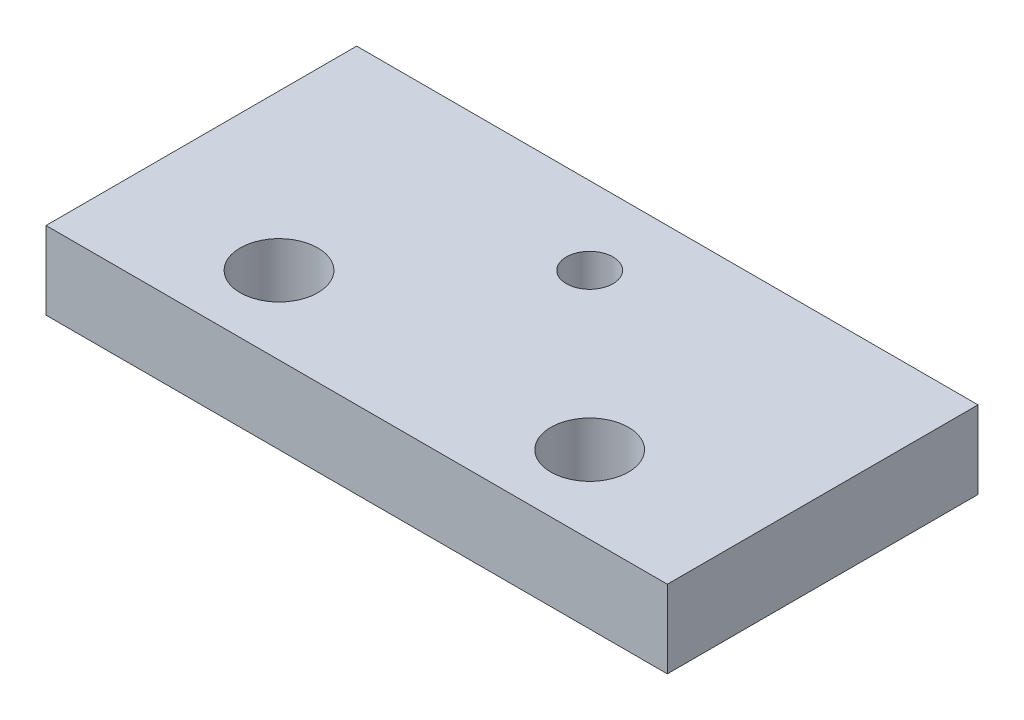
SolidWorks part; units mm, degrees
ref_plane "Front Plane" through (0, 0, 0) normal (0, 0, 1) x (1, 0, 0)
ref_plane "Top Plane" through (0, 0, 0) normal (0, 1, 0) x (1, 0, 0)
ref_plane "Right Plane" through (0, 0, 0) normal (1, 0, 0) x (0, 0, -1)
sketch "Sketch1" plane through (0, 0, 0) normal (0, 1, 0) x (1, 0, 0)
  line L1 (0, 0) -> (25.4, 0)
  line L2 (0, 0) -> (0, 12.7)
  line L3 (0, 12.7) -> (25.4, 12.7)
  line L4 (25.4, 0) -> (25.4, 12.7)
  dimension "D1" = 25.4
  dimension "D2" = 12.7
extrude "Boss-Extrude1" add sketch "Sketch1" along normal blind 3.175
sketch "Sketch2" plane through (0, 3.175, 0) normal (0, 1, 0) x (1, 0, 0)
  line L0 (12.7, 12.7) -> (12.7, 0) construction
  line L1 (25.4, 12.7) -> (0, 12.7) construction
  line L2 (0, 0) -> (25.4, 0) construction
  circle A0 centre (19.05, 3.175) radius 1.5875
  circle A1 centre (6.35, 3.175) radius 1.5875
  circle A2 centre (12.7, 9.525) radius 0.9525
  dimension "D1" = 6.35
  dimension "D2" = 3.175
  dimension "D3" = 3.175
  dimension "D4" = 1.905
  dimension "D5" = 9.525
extrude "Cut-Extrude1" cut sketch "Sketch2" against normal through all
